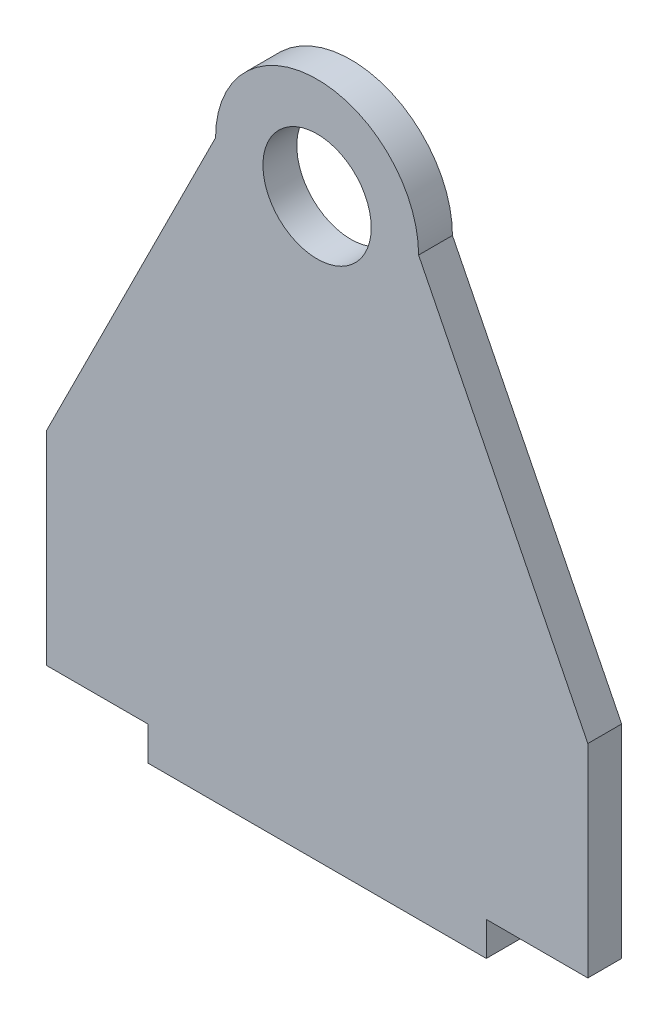
SolidWorks part; units mm, degrees
ref_plane "Front Plane" through (0, 0, 0) normal (0, 0, 1) x (1, 0, 0)
ref_plane "Top Plane" through (0, 0, 0) normal (0, 1, 0) x (1, 0, 0)
ref_plane "Right Plane" through (0, 0, 0) normal (1, 0, 0) x (0, 0, -1)
sketch "Sketch1" plane through (0, 0, 0) normal (0, 0, 1) x (1, 0, 0)
  line L0 (-40, -80) -> (-25, -80)
  line L1 (25, -80) -> (40, -80)
  line L2 (0, -80) -> (0, -74.8605) construction
  line L4 (40, -80) -> (40, -50)
  line L5 (40, -50) -> (15, 0)
  line L6 (-40, -80) -> (-40, -50)
  line L7 (-40, -50) -> (-15, 0)
  line L8 (-25, -80) -> (-25, -85)
  line L9 (-25, -85) -> (25, -85)
  line L10 (25, -80) -> (25, -85)
  circle A0 centre (0, 0) radius 8
  arc A1 (15, 0) -> (-15, 0) centre (0, 0) ccw
  dimension "D1" = 16
  dimension "D2" = 30
  dimension "D3" = 40
  dimension "D4" = 80
  dimension "D5" = 30
  dimension "D6" = 5
  dimension "D7" = 15
  dimension "D8" = 15
  dimension "D9" = 25
extrude "Boss-Extrude1" add sketch "Sketch1" along normal blind 5
